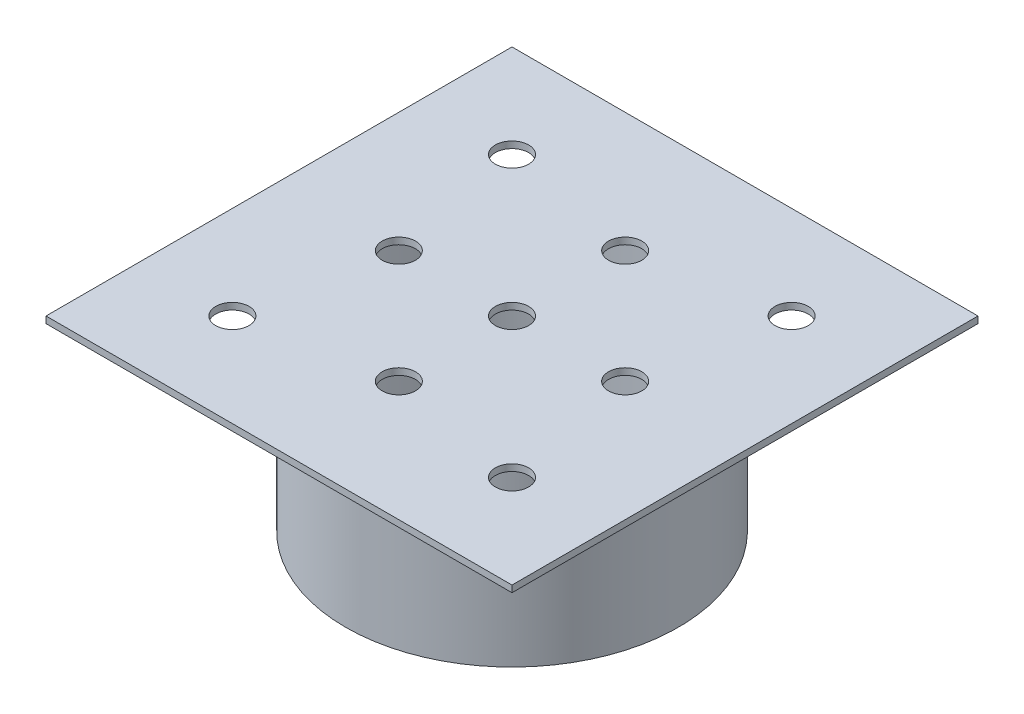
SolidWorks part; units mm, degrees
material "Plain Carbon Steel"
ref_plane "Front Plane" through (0, 0, 0) normal (0, 0, 1) x (1, 0, 0)
ref_plane "Top Plane" through (0, 0, 0) normal (0, 1, 0) x (1, 0, 0)
ref_plane "Right Plane" through (0, 0, 0) normal (1, 0, 0) x (0, 0, -1)
sketch "Sketch1" plane through (0, 0, 0) normal (0, 1, 0) x (1, 0, 0)
  line L1 (-35, 35) -> (35, 35)
  line L2 (-35, 35) -> (-35, -35)
  line L3 (-35, -35) -> (35, -35)
  line L4 (35, 35) -> (35, -35)
  line L5 (-35, 35) -> (35, -35) construction
  line L6 (-35, -35) -> (35, 35) construction
  point P0 (0, 0)
  dimension "D1" = 70
  dimension "D2" = 70
extrude "Boss-Extrude1" add sketch "Sketch1" along normal blind 1
sketch "Sketch2" plane through (0, 0, 0) normal (0, -1, 0) x (1, 0, 0)
  circle A0 centre (0, 0) radius 25
  circle A1 centre (0, 0) radius 23
  dimension "D1" = 50
  dimension "D2" = 2
extrude "Boss-Extrude2" add sketch "Sketch2" along normal blind 27
sketch "Sketch3" plane through (0, 1, 0) normal (0, 1, 0) x (1, 0, 0)
  circle A0 centre (0, 0) radius 2.5
  circle A1 centre (0, 0) radius 17 construction
  circle A2 centre (0, 17) radius 2.5
  circle A3 centre (17, 0) radius 2.5
  circle A4 centre (0, -17) radius 2.5
  circle A5 centre (-17, 0) radius 2.5
  point P15 (0, 0)
  dimension "D1" = 4
extrude "Cut-Extrude1" cut sketch "Sketch3" against normal blind 1
sketch "Sketch4" plane through (0, 1, 0) normal (0, 1, 0) x (1, 0, 0)
  line L0 (35, 35) -> (-35, 35) construction
  line L1 (-35, 35) -> (-35, -35) construction
  circle A3 centre (0, 0) radius 29.6985 construction
  circle A5 centre (21, 21) radius 2.5
  circle A7 centre (21, -21) radius 2.5
  circle A8 centre (-21, 21) radius 2.5
  circle A9 centre (-21, -21) radius 2.5
  point P16 (0, 0)
  point P22 (0, 0)
  dimension "D1" = 14
  dimension "D2" = 14
  dimension "D3" = 4
extrude "Cut-Extrude2" cut sketch "Sketch4" against normal blind 1
